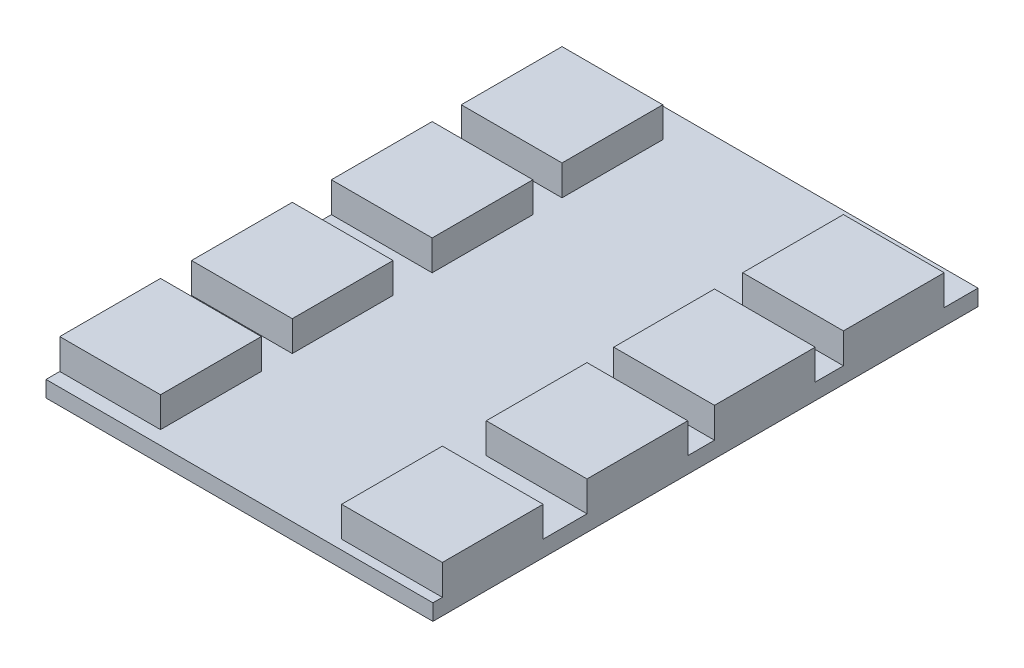
SolidWorks part; units mm, degrees
ref_plane "Front Plane" through (0, 0, 0) normal (0, 0, 1) x (1, 0, 0)
ref_plane "Top Plane" through (0, 0, 0) normal (0, 1, 0) x (1, 0, 0)
ref_plane "Right Plane" through (0, 0, 0) normal (1, 0, 0) x (0, 0, -1)
sketch "Эскиз1" plane through (0, 0, 0) normal (0, 1, 0) x (1, 0, 0)
  line L1 (-19.2, -27.05) -> (19.2, -27.05)
  line L2 (-19.2, -27.05) -> (-19.2, 27.05)
  line L3 (-19.2, 27.05) -> (19.2, 27.05)
  line L4 (19.2, -27.05) -> (19.2, 27.05)
  line L5 (-19.2, -27.05) -> (19.2, 27.05) construction
  line L6 (-19.2, 27.05) -> (19.2, -27.05) construction
  point P0 (0, 0)
  dimension "D1" = 54.1
  dimension "D2" = 38.4
extrude "Бобышка-Вытянуть1" add sketch "Эскиз1" along normal mid plane 1.6
sketch "Эскиз2" plane through (0, 0.8, 0) normal (0, 1, 0) x (1, 0, 0)
  line L0 (-19.2, 27.05) -> (-19.2, -27.05) construction
  line L1 (-19.2, 24.1646) -> (-9.2, 24.1646)
  line L2 (-19.2, 24.1646) -> (-19.2, 14.1646)
  line L3 (-19.2, 14.1646) -> (-9.2, 14.1646)
  line L4 (-9.2, 24.1646) -> (-9.2, 14.1646)
  line L5 (19.2, -27.05) -> (19.2, 27.05) construction
  line L6 (-19.2, 11.2748) -> (-9.2, 11.2748)
  line L7 (-19.2, 11.2748) -> (-19.2, 1.2748)
  line L8 (-19.2, 1.2748) -> (-9.2, 1.2748)
  line L9 (-9.2, 11.2748) -> (-9.2, 1.2748)
  line L10 (-19.2, -2.6065) -> (-9.2, -2.6065)
  line L11 (-19.2, -2.6065) -> (-19.2, -12.6065)
  line L12 (-19.2, -12.6065) -> (-9.2, -12.6065)
  line L13 (-9.2, -2.6065) -> (-9.2, -12.6065)
  line L14 (-19.2, -15.6852) -> (-9.2, -15.6852)
  line L15 (-19.2, -15.6852) -> (-19.2, -25.6852)
  line L16 (-19.2, -25.6852) -> (-9.2, -25.6852)
  line L17 (-9.2, -15.6852) -> (-9.2, -25.6852)
  line L18 (19.2, 23.6925) -> (9.2, 23.6925)
  line L19 (19.2, 23.6925) -> (19.2, 13.6925)
  line L20 (19.2, 13.6925) -> (9.2, 13.6925)
  line L21 (9.2, 23.6925) -> (9.2, 13.6925)
  line L23 (19.2, 10.8971) -> (9.2, 10.8971)
  line L24 (19.2, 10.8971) -> (19.2, 0.8971)
  line L25 (19.2, 0.8971) -> (9.2, 0.8971)
  line L26 (9.2, 10.8971) -> (9.2, 0.8971)
  line L27 (19.2, -1.7566) -> (9.2, -1.7566)
  line L28 (19.2, -1.7566) -> (19.2, -11.7566)
  line L29 (19.2, -11.7566) -> (9.2, -11.7566)
  line L30 (9.2, -1.7566) -> (9.2, -11.7566)
  line L31 (19.2, -16.1101) -> (9.2, -16.1101)
  line L32 (19.2, -16.1101) -> (19.2, -26.1101)
  line L33 (19.2, -26.1101) -> (9.2, -26.1101)
  line L34 (9.2, -16.1101) -> (9.2, -26.1101)
  dimension "D1" = 10
  dimension "D2" = 10
extrude "Бобышка-Вытянуть2" add sketch "Эскиз2" along normal blind 3
